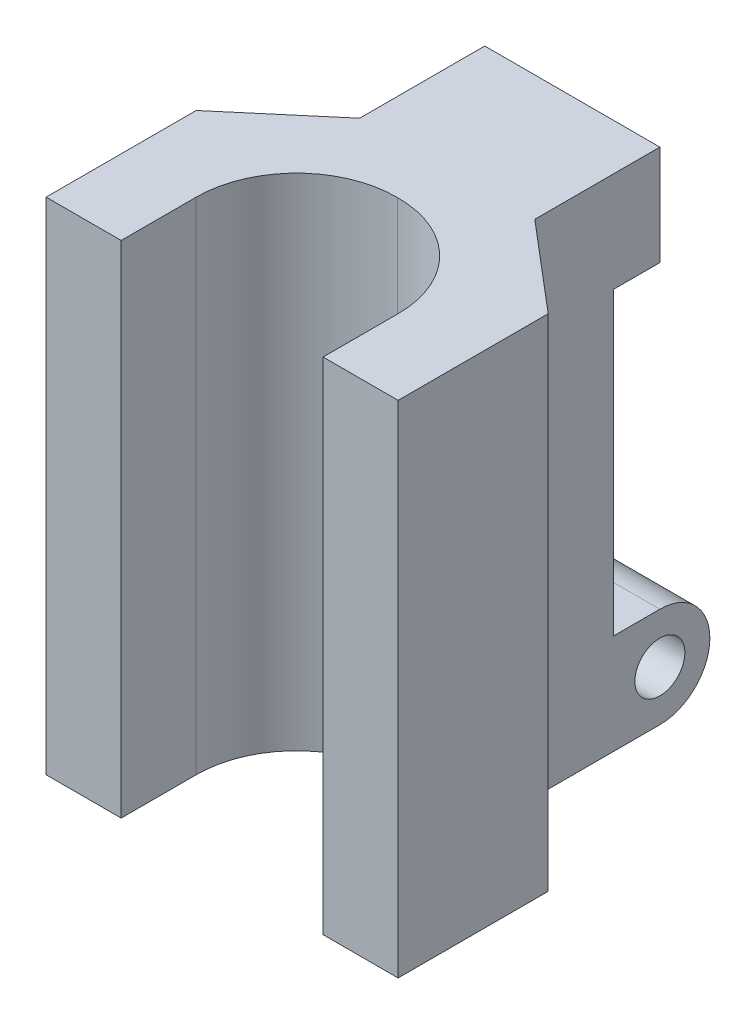
SolidWorks part; units mm, degrees
ref_plane "Front Plane" through (0, 0, 0) normal (0, 0, 1) x (1, 0, 0)
ref_plane "Top Plane" through (0, 0, 0) normal (0, 1, 0) x (1, 0, 0)
ref_plane "Right Plane" through (0, 0, 0) normal (1, 0, 0) x (0, 0, -1)
sketch "Sketch1" plane through (0, 0, 0) normal (0, 1, 0) x (1, 0, 0)
  line L0 (22.225, 0) -> (-22.225, 0)
  line L1 (-22.225, 0) -> (-44.6768, -19.05)
  line L2 (-44.6768, -19.05) -> (-44.6768, -57.15)
  line L3 (-44.6768, -57.15) -> (-25.6268, -57.15)
  line L4 (-25.6268, -57.15) -> (-25.6268, -38.1)
  line L6 (22.225, 0) -> (44.6768, -19.05)
  line L7 (44.6768, -19.05) -> (44.6768, -57.15)
  line L8 (44.6768, -57.15) -> (25.6268, -57.15)
  line L9 (25.6268, -57.15) -> (25.6268, -38.1)
  arc A0 (-25.6268, -38.1) -> (0, -12.6572) centre (-0.2268, -38.0562) cw
  arc A1 (25.6268, -38.1) -> (0, -12.6572) centre (0.2268, -38.0562) ccw
  dimension "D2" = 25.4
  dimension "D4" = 19.05
  dimension "D5" = 19.05
  dimension "D6" = 38.1
  dimension "D7" = 57.15
extrude "Boss-Extrude1" add sketch "Sketch1" against normal blind 127 contours A1 L9 L8 L7 L6 L0 L1 L2 L3 L4 A0
ref_plane "Plane1" through (-22.225, 0, 0) normal (-1, 0, 0) x (0, 1, 0)
sketch "Sketch2" plane through (-22.225, 0, 0) normal (-1, 0, 0) x (0, 1, 0)
  line L0 (-127, 0) -> (-127, 31.75)
  line L2 (-101.6, 31.75) -> (-101.6, 20.0062)
  line L3 (-101.6, 20.0062) -> (-25.4, 20.0062)
  line L4 (-25.4, 20.0062) -> (-25.4, 31.75)
  line L5 (-25.4, 31.75) -> (0, 31.75)
  line L6 (0, 31.75) -> (0, 0)
  line L7 (0, 0) -> (-127, 0)
  arc A0 (-127, 31.75) -> (-101.6, 31.75) centre (-114.3, 31.75) cw
  circle A1 centre (-114.3, 31.75) radius 6.35
  dimension "D4" = 12.7
  dimension "D5" = 12.7
  dimension "D1" = 31.75
  dimension "D2" = 31.75
  dimension "D3" = 25.4
extrude "Boss-Extrude3" add sketch "Sketch2" against normal blind 44.45
ref_plane "Plane2" through (-44.6768, 0, 0) normal (-1, 0, 0) x (0, 0, 1)
sketch "Sketch8" plane through (-44.6768, 0, 0) normal (-1, 0, 0) x (0, 0, 1)
  line L0 (57.15, -127) -> (57.15, 0) construction
  line L1 (57.15, -102.337) -> (0, -102.337)
  line L2 (57.15, -102.337) -> (57.15, -26.1339)
  line L3 (57.15, -26.1339) -> (0, -26.1339)
  line L4 (0, -102.337) -> (0, -26.1339)
  line L5 (0, 0) -> (0, -127) construction
  line L6 (19.05, 0) -> (57.15, 0) construction
  point P8 (0, -56.2145)
  point P9 (0, -102.337)
  point P10 (57.15, -26.1339)
  dimension "D1" = 26.1339
